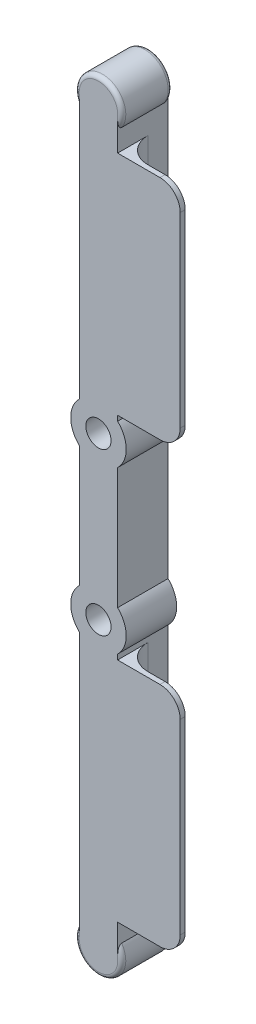
SolidWorks part; units mm, degrees
ref_plane "Front Plane" through (0, 0, 0) normal (0, 0, 1) x (1, 0, 0)
ref_plane "Top Plane" through (0, 0, 0) normal (0, 1, 0) x (1, 0, 0)
ref_plane "Right Plane" through (0, 0, 0) normal (1, 0, 0) x (0, 0, -1)
sketch "Sketch1" plane through (0, 0, 0) normal (0, 0, 1) x (1, 0, 0)
  line L0 (0, 0) -> (0, 44.9793) construction
  line L5 (3.8, 0) -> (-3.8, 0)
  line L6 (-3.8, 0) -> (-3.8, 6)
  line L7 (-3.8, 6) -> (-9.3, 6)
  line L8 (-9.3, 6) -> (-9.3, 9.28)
  line L9 (-9.3, 9.28) -> (-4.8, 13.8308)
  line L10 (-4.8, 13.8308) -> (4.8, 13.8308)
  line L11 (0, 13.8308) -> (0, 0) construction
  line L12 (9.3, 9.28) -> (4.8, 13.8308)
  line L13 (9.3, 6) -> (9.3, 9.28)
  line L14 (3.8, 6) -> (9.3, 6)
  line L15 (3.8, 0) -> (3.8, 6)
  line L17 (3.8, 0) -> (-3.8, 0)
  line L18 (3.8, 0) -> (3.8, -64)
  line L19 (3.8, -64) -> (-3.8, -64)
  line L20 (-3.8, 0) -> (-3.8, -64)
  line L21 (3.8, 0) -> (-3.8, -64) construction
  line L22 (3.8, -64) -> (-3.8, 0) construction
  circle A0 centre (0, 8.6308) radius 4.6218
  circle A1 centre (0, -48) radius 2.5
  arc A2 (3.8, -44.0238) -> (3.8, -51.9762) centre (0, -48) cw
  arc A3 (-3.8, -44.0238) -> (-3.8, -51.9762) centre (0, -48) ccw
  point P21 (0, -32)
  dimension "D7" = 5.2
  dimension "D9" = 5
  dimension "D11" = 5.5
  dimension "D1" = 3.8
  dimension "D2" = 6
  dimension "D3" = 5.5
  dimension "D4" = 3.28
  dimension "D5" = 6.4
  dimension "D6" = 4.8
  dimension "D8" = 70
  dimension "D10" = 16
extrude "Boss-Extrude1" add sketch "Sketch1" along normal blind 10 contours A0 | A0 L6 L5 L15 | L5 L20 L19 L18 | A2 L18 | L20 A3
ref_plane "Plane1" through (0, -64, 0) normal (0, -1, 0) x (-1, 0, 0)
sketch "Sketch4" plane through (0, 0, 10) normal (0, 0, 1) x (1, 0, 0)
  line L0 (0, 0) -> (0, -67.9118) construction
  line L1 (-3.8, -44.0238) -> (-3.8, 6) construction
  line L6 (-3.8, -43) -> (16.2, -43)
  line L7 (-3.8, -43) -> (-3.8, 2)
  line L8 (-3.8, 2) -> (16.2, 2)
  line L9 (16.2, -43) -> (16.2, 2)
  line L10 (-3.8, -43) -> (16.2, 2) construction
  line L11 (-3.8, 2) -> (16.2, -43) construction
  point P9 (6.2, -20.5)
  dimension "D1" = 20
  dimension "D2" = 45
  dimension "D3" = 2
extrude "Boss-Extrude2" add sketch "Sketch4" against normal blind 1
fillet "Fillet3" radius 0.8 2 edges at (0, 13.2526, 0) (0, 13.2526, 10)
fillet "Fillet2" radius 4 2 edges at (16.2, 2, 9.5) (16.2, -43, 9.5)
fillet "Fillet1" radius 5 1 edges at (3.8, -20.5, 9)
mirror "Mirror1" about plane through (0, -64, 0) normal (0, -1, 0) of "Fillet3", "Boss-Extrude2", "Fillet1", "Boss-Extrude1", "Fillet2"
